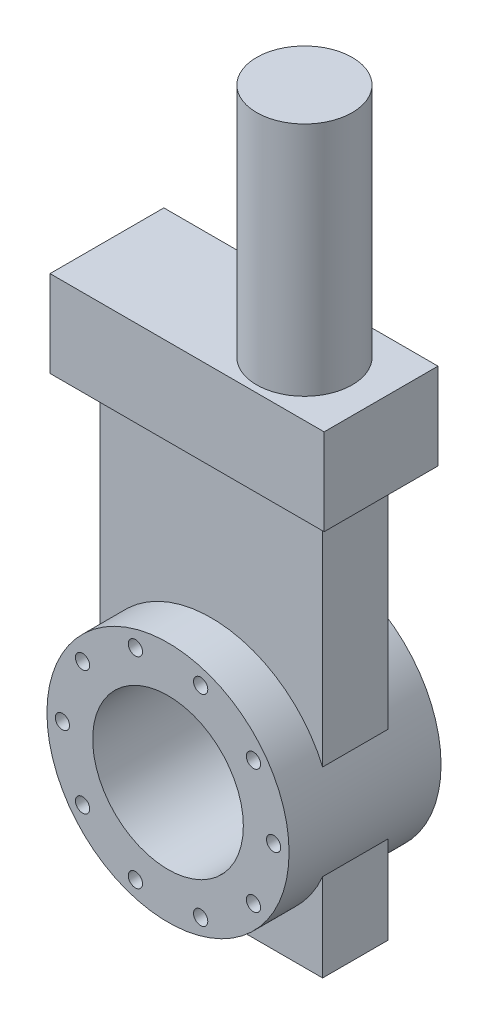
SolidWorks part; units mm, degrees
ref_plane "Front Plane" through (0, 0, 0) normal (0, 0, 1) x (1, 0, 0)
ref_plane "Top Plane" through (0, 0, 0) normal (0, 1, 0) x (1, 0, 0)
ref_plane "Right Plane" through (0, 0, 0) normal (1, 0, 0) x (0, 0, -1)
sketch "Sketch1" plane through (0, 0, 0) normal (0, 0, 1) x (1, 0, 0)
  line L1 (-29.1963, 27.7605) -> (78.7537, 27.7605)
  line L2 (-29.1963, 27.7605) -> (-29.1963, -192.5845)
  line L3 (-29.1963, -192.5845) -> (78.7537, -192.5845)
  line L4 (78.7537, 27.7605) -> (78.7537, -192.5845)
  dimension "D1" = 107.95
  dimension "D2" = 220.345
extrude "Extrude1" add sketch "Sketch1" along normal blind 31.75
sketch "Sketch2" plane through (0, 0, 31.75) normal (0, 0, 1) x (1, 0, 0)
  line L0 (24.7787, 11.5045) -> (24.7787, -208.8405) construction
  line L1 (-79.3719, -185.7265) -> (90.4007, -185.7265) construction
  line L2 (78.7537, 27.7605) -> (-29.1963, 27.7605) construction
  line L3 (-29.1963, -192.5845) -> (78.7537, -192.5845) construction
  circle A0 centre (24.7787, -127.0525) radius 58.674
  point P4 (24.7787, 27.7605)
  dimension "D1" = 117.348
  dimension "D2" = 65.532
extrude "Extrude2" add sketch "Sketch2" along normal blind 20.955 and the other way blind 52.705
sketch "Sketch3" plane through (0, 0, 52.705) normal (0, 0, 1) x (1, 0, 0)
  circle A0 centre (24.7787, -127.0525) radius 36.5125
  dimension "D1" = 73.025
extrude "Extrude3" cut sketch "Sketch3" against normal through all
sketch "Sketch4" plane through (0, 0, 52.705) normal (0, 0, 1) x (1, 0, 0)
  line L0 (24.7787, -72.0489) -> (24.7787, -189.3969) construction
  point P0 (24.7787, -127.0525)
hole_wizard "5/16-24 Tapped Hole1" positions "Sketch6" profile "Sketch5" tap size "5/16-24" standard "Ansi Inch" end condition through all
sketch "Sketch6" plane through (0, 0, 52.705) normal (0, 0, 1) x (1, 0, 0)
  line L0 (8.9629, -78.3765) -> (24.7787, -127.0525) construction
  line L2 (24.7787, 199927.9511) -> (24.7787, -200189.3969) construction
  point P0 (8.9629, -78.3765)
  dimension "D1" = 51.181
  dimension "D2" = 18
sketch "Sketch5" plane through (8.9629, -78.3765, 52.705) normal (1, 0, 0) x (0, -1, 0)
  line L0 (0, 0) -> (0, 73.66)
  line L1 (0, 73.66) -> (3.4544, 73.66)
  line L2 (3.4544, 73.66) -> (3.4544, 0)
  line L5 (3.4544, 0) -> (0, 0)
  line L11 (0, -6.35) -> (0, 107.95) construction
  dimension "Thru Tap Drill Dia." = 6.9088
  dimension "Thru Tap Drill Depth" = 73.66
cosmetic thread "Hole Thread1" parameters "D2"=7.9375
pattern_circular "CirPattern1" count 10 over 360 about axis through (24.7787, -127.0525, 0) along (0, 0, 1) of "5/16-24 Tapped Hole1"
sketch "Sketch7" plane through (0, 27.7605, 0) normal (0, 1, 0) x (1, 0, 0)
  line L0 (24.7787, 0) -> (24.7787, -31.75) construction
  line L3 (78.7537, 0) -> (-29.1963, 0) construction
  line L6 (-29.1963, -31.75) -> (78.7537, -31.75) construction
  line L7 (-29.1963, -15.875) -> (78.7537, -15.875) construction
  line L8 (-29.1963, -31.75) -> (-29.1963, 0) construction
  line L9 (78.7537, -31.75) -> (78.7537, 0) construction
  line L11 (91.1997, 11.7114) -> (-41.6423, 11.7114)
  line L12 (-41.6423, 11.7114) -> (-41.6423, -43.4614)
  line L13 (91.1997, 11.7114) -> (91.1997, -43.4614)
  line L14 (91.1997, -43.4614) -> (-41.6423, -43.4614)
  point P12 (24.7787, -43.4614)
  point P17 (24.7787, 11.7114)
  point P19 (91.1997, -15.875)
  point P20 (-41.6423, -15.875)
  dimension "D1" = 132.842
extrude "Extrude4" add sketch "Sketch7" along normal blind 20.955 and the other way blind 20.955
sketch "Sketch8" plane through (0, 48.7155, 0) normal (0, 1, 0) x (1, 0, 0)
  circle A0 centre (55.1442, -16.9467) radius 23.1746
extrude "Extrude5" add sketch "Sketch8" along normal blind 114.3
